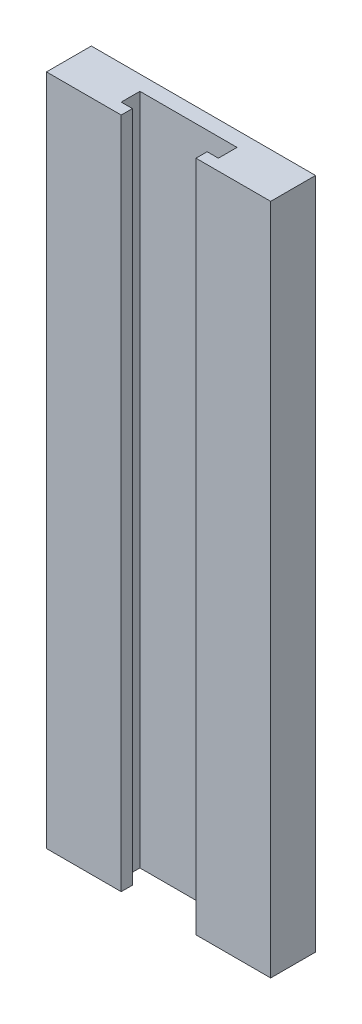
SolidWorks part; units mm, degrees
ref_plane "Front Plane" through (0, 0, 0) normal (0, 0, 1) x (1, 0, 0)
ref_plane "Top Plane" through (0, 0, 0) normal (0, 1, 0) x (1, 0, 0)
ref_plane "Right Plane" through (0, 0, 0) normal (1, 0, 0) x (0, 0, -1)
sketch "Sketch1" plane through (0, 0, 0) normal (0, 0, 1) x (1, 0, 0)
  line L1 (-8, 25) -> (8, 25)
  line L2 (-8, 25) -> (-8, -65)
  line L3 (-8, -65) -> (8, -65)
  line L4 (8, 25) -> (8, -65)
  dimension "D1" = 16
  dimension "D2" = 90
  dimension "D3" = 65
  dimension "D4" = 8
extrude "Boss-Extrude1" add sketch "Sketch1" along normal blind 2
sketch "Sketch2" plane through (0, 0, 2) normal (0, 0, 1) x (1, 0, 0)
  line L0 (-8, -65) -> (8, -65) construction
  line L1 (-8, 25) -> (-6.5, 25)
  line L2 (-8, 25) -> (-8, -65)
  line L3 (-8, -65) -> (-6.5, -65)
  line L4 (-6.5, 25) -> (-6.5, -65)
  line L5 (0, 66.6255) -> (0, -75.3276) construction
  line L6 (8, -65) -> (6.5, -65)
  line L7 (8, 25) -> (6.5, 25)
  line L8 (6.5, 25) -> (6.5, -65)
  line L9 (8, 25) -> (8, -65)
  dimension "D1" = 1.5
extrude "Boss-Extrude2" add sketch "Sketch2" along normal blind 4
sketch "Sketch3" plane through (-6.5, 0, 0) normal (1, 0, 0) x (0, 0, -1)
  line L0 (-6, -65) -> (0, -65) construction
  line L1 (-6, 25) -> (-4.5, 25)
  line L2 (-6, 25) -> (-6, -65)
  line L3 (-6, -65) -> (-4.5, -65)
  line L4 (-4.5, 25) -> (-4.5, -65)
  dimension "D1" = 1.5
extrude "Boss-Extrude3" add sketch "Sketch3" along normal blind 1.5
sketch "Sketch4" plane through (6.5, 0, 0) normal (-1, 0, 0) x (0, 0, 1)
  line L1 (6, 25) -> (4.5, 25)
  line L2 (6, 25) -> (6, -65)
  line L3 (6, -65) -> (4.5, -65)
  line L4 (4.5, 25) -> (4.5, -65)
extrude "Boss-Extrude4" add sketch "Sketch4" along normal blind 1.5
ref_plane "Plane1" through (5, 0, 0) normal (-1, 0, 0) x (0, 0, 1)
sketch "Sketch5" plane through (0, 0, 2) normal (0, 0, 1) x (1, 0, 0)
  line L0 (5, 93.3535) -> (5, -85.176) construction
  line L1 (5, 1.375) -> (5, -1.375) construction
sketch "Sketch6" plane through (8, 0, 0) normal (1, 0, 0) x (0, 0, -1)
  line L1 (0, 25) -> (-6, 25)
  line L2 (0, 25) -> (0, -65)
  line L3 (0, -65) -> (-6, -65)
  line L4 (-6, 25) -> (-6, -65)
extrude "Boss-Extrude5" add sketch "Sketch6" along normal blind 7
sketch "Sketch7" plane through (-8, 0, 0) normal (-1, 0, 0) x (0, 0, 1)
  line L4 (0, 25) -> (0, -65)
  line L5 (0, -65) -> (6, -65)
  line L6 (6, -65) -> (6, 25)
  line L7 (6, 25) -> (0, 25)
  line L8 (0, 25) -> (0, -65)
  line L9 (0, -65) -> (6, -65)
  line L10 (6, -65) -> (6, 25)
  line L11 (6, 25) -> (0, 25)
  dimension "D1" = 0
extrude "Boss-Extrude6" add sketch "Sketch7" along normal blind 7
